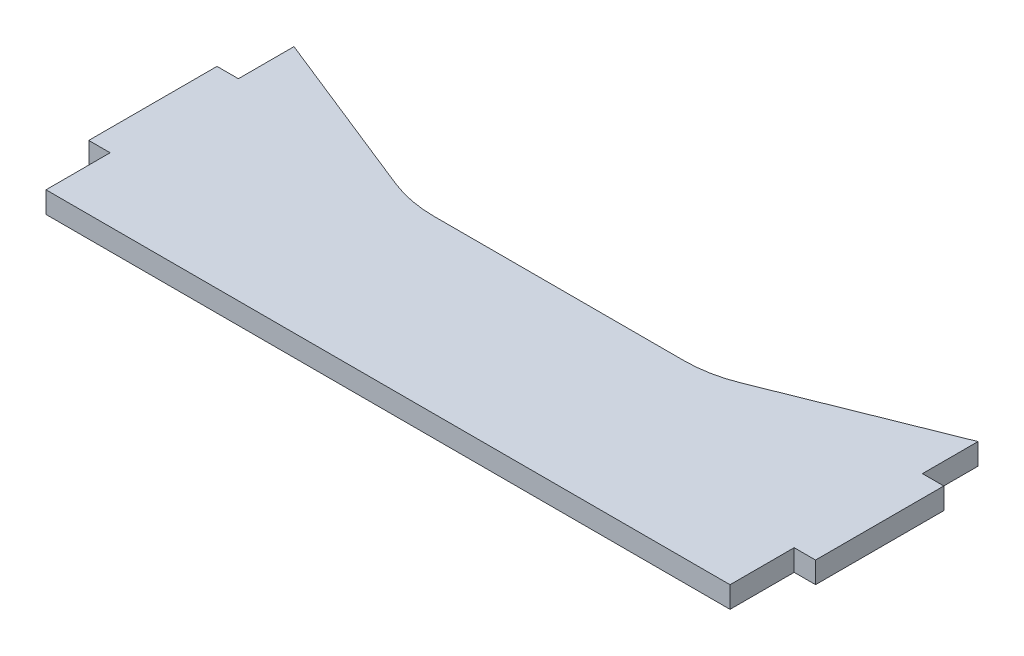
SolidWorks part; units mm, degrees
ref_plane "정면" through (0, 0, 0) normal (0, 0, 1) x (1, 0, 0)
ref_plane "윗면" through (0, 0, 0) normal (0, 1, 0) x (1, 0, 0)
ref_plane "우측면" through (0, 0, 0) normal (1, 0, 0) x (0, 0, -1)
sketch "스케치1" plane through (0, 0, 0) normal (0, 1, 0) x (1, 0, 0)
  line L1 (0, 0) -> (170, 0)
  line L2 (0, 0) -> (0, 40)
  line L3 (0, 40) -> (170, 40)
  line L4 (170, 0) -> (170, 40)
  dimension "D1" = 170
  dimension "D2" = 40
extrude "보스-돌출1" add sketch "스케치1" along normal blind 5
sketch "스케치2" plane through (0, 5, 0) normal (0, 1, 0) x (1, 0, 0)
  line L0 (170, 40) -> (170, 60)
  line L1 (170, 60) -> (120, 40)
  line L2 (170, 40) -> (0, 40) construction
  line L3 (120, 40) -> (170, 40)
  line L4 (0, 40) -> (0, 60)
  line L5 (0, 60) -> (50, 40)
  line L6 (50, 40) -> (0, 40)
  dimension "D1" = 50
  dimension "D2" = 50
  dimension "D3" = 20
  dimension "D4" = 20
extrude "보스-돌출2" add sketch "스케치2" against normal blind 5
fillet "필렛1" radius 30 2 edges at (50, 2.5, -40)
sketch "스케치3" plane through (0, 0, 0) normal (0, -1, 0) x (-1, 0, 0)
  line L1 (-5, 45) -> (0, 45)
  line L2 (-5, 45) -> (-5, 60)
  line L3 (-5, 60) -> (0, 60)
  line L4 (0, 45) -> (0, 60)
  line L5 (-5, 15) -> (0, 15)
  line L6 (-5, 15) -> (-5, 0)
  line L7 (-5, 0) -> (0, 0)
  line L8 (0, 15) -> (0, 0)
  line L9 (-165, 45) -> (-170, 45)
  line L10 (-165, 45) -> (-165, 60)
  line L11 (-165, 60) -> (-170, 60)
  line L12 (-170, 45) -> (-170, 60)
  line L13 (-165, 15) -> (-170, 15)
  line L14 (-165, 15) -> (-165, 0)
  line L15 (-165, 0) -> (-170, 0)
  line L16 (-170, 15) -> (-170, 0)
extrude "컷-돌출1" cut sketch "스케치3" against normal blind 10
